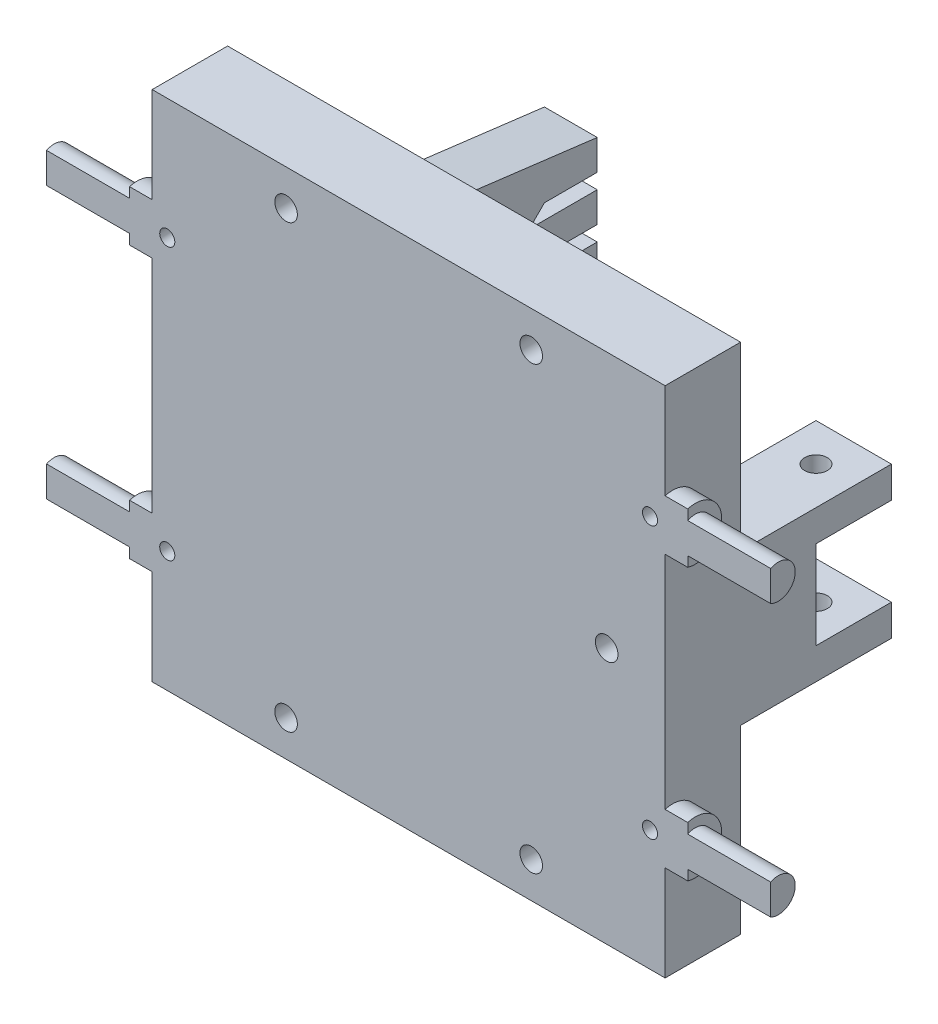
SolidWorks part; units mm, degrees
ref_plane "Front Plane" through (0, 0, 0) normal (0, 0, 1) x (1, 0, 0)
ref_plane "Top Plane" through (0, 0, 0) normal (0, 1, 0) x (1, 0, 0)
ref_plane "Right Plane" through (0, 0, 0) normal (1, 0, 0) x (0, 0, -1)
sketch "Sketch1" plane through (0, 0, 0) normal (0, 0, 1) x (1, 0, 0)
  line L1 (0, 0) -> (-68, 0)
  line L2 (0, 0) -> (0, -68)
  line L3 (0, -68) -> (-68, -68)
  line L4 (-68, 0) -> (-68, -68)
  dimension "D1" = 68
  dimension "D2" = 68
extrude "Boss-Extrude1" add sketch "Sketch1" along normal blind 10
sketch "Sketch2" plane through (-68, 0, 0) normal (-1, 0, 0) x (0, 0, 1)
  line L1 (10, 0) -> (0, 0) construction
  line L2 (10, -68) -> (0, -68) construction
  line L3 (10, 0) -> (10, -68) construction
  line L4 (10, 0) -> (10, -68)
  circle A0 centre (9, -52) radius 3.5
  circle A1 centre (9, -16) radius 3.5
  dimension "D1" = 7
  dimension "D2" = 7
  dimension "D3" = 1
  dimension "D4" = 0
  dimension "D5" = 16
  dimension "D6" = 16
extrude "Boss-Extrude2" add sketch "Sketch2" along normal blind 3 contours L4 A1 | L4 A0
sketch "Sketch3" plane through (-71, 0, 0) normal (-1, 0, 0) x (0, 0, 1)
  line L0 (10, -55.3541) -> (10, -12.6459)
  circle A0 centre (9, -52) radius 2.25
  circle A1 centre (9, -16) radius 2.25
  dimension "D1" = 4.5
  dimension "D2" = 4.5
extrude "Boss-Extrude3" add sketch "Sketch3" along normal blind 11 contours L0 A0 | L0 A1
sketch "Sketch4" plane through (0, 0, 0) normal (1, 0, 0) x (0, 0, -1)
  line L0 (-10, 0) -> (0, 0) construction
  line L1 (-10, -68) -> (0, -68) construction
  line L2 (-10, 0) -> (-10, -68)
  circle A0 centre (-9, -16) radius 3.5
  circle A1 centre (-9, -52) radius 3.5
  dimension "D1" = 16
  dimension "D2" = 16
  dimension "D3" = 7
  dimension "D4" = 7
  dimension "D5" = 1
  dimension "D6" = 0
extrude "Boss-Extrude4" add sketch "Sketch4" along normal blind 3 contours L2 A0 | L2 A1
sketch "Sketch5" plane through (3, 0, 0) normal (1, 0, 0) x (0, 0, -1)
  line L0 (-10, -12.6459) -> (-10, -55.3541)
  circle A0 centre (-9, -16) radius 2.25
  circle A1 centre (-9, -52) radius 2.25
  dimension "D1" = 4.5
  dimension "D2" = 4.5
extrude "Boss-Extrude5" add sketch "Sketch5" along normal blind 11 contours L0 A0 | L0 A1
sketch "Sketch6" plane through (0, 0, 0) normal (0, 0, -1) x (-1, 0, 0)
  line L0 (0, -34) -> (68, -34) construction
  line L1 (55.25, -12.75) -> (12.75, -12.75)
  line L2 (55.25, -12.75) -> (55.25, -55.25)
  line L3 (55.25, -55.25) -> (12.75, -55.25)
  line L4 (12.75, -12.75) -> (12.75, -55.25)
  line L5 (0, -68) -> (0, 0) construction
  line L6 (68, 0) -> (68, -68) construction
  line L7 (34, 0) -> (34, -68) construction
  line L8 (0, 0) -> (68, 0) construction
  line L9 (68, -68) -> (0, -68) construction
  point P16 (12.75, -34)
  point P17 (34, -55.25)
  dimension "D1" = 42.5
  dimension "D2" = 42.5
  dimension "D3" = 0
  dimension "D4" = 0
extrude "Cut-Extrude1" cut sketch "Sketch6" against normal blind 3
sketch "Sketch8" plane through (0, 0, 0) normal (0, 0, -1) x (-1, 0, 0)
  line L0 (55.25, -12.75) -> (12.75, -12.75) construction
  line L2 (12.75, -12.75) -> (12.75, -55.25) construction
  line L3 (34, 0) -> (34, -108.8236) construction
  line L4 (0, 0) -> (68, 0) construction
  line L5 (0, -34) -> (112.3527, -34) construction
  line L6 (0, -68) -> (0, 0) construction
  circle A0 centre (17.75, -4.75) radius 1.5
  circle A3 centre (50.25, -4.75) radius 1.5
  circle A4 centre (50.25, -63.25) radius 1.5
  circle A5 centre (17.75, -63.25) radius 1.5
  dimension "D1" = 8
  dimension "D3" = 3
  dimension "D5" = 5
extrude "Cut-Extrude2" cut sketch "Sketch8" against normal blind 15
sketch "Sketch9" plane through (0, 0, 0) normal (0, 0, -1) x (-1, 0, 0)
  line L1 (0, -24) -> (10, -24)
  line L2 (0, -24) -> (0, -44)
  line L3 (0, -44) -> (10, -44)
  line L4 (10, -24) -> (10, -44)
  line L6 (0, -68) -> (0, 0) construction
  point P4 (0, -34)
  point P7 (0, -34)
  dimension "D1" = 0
  dimension "D2" = 20
  dimension "D3" = 0
  dimension "D4" = 10
  dimension "D5" = 90
  dimension "D6" = 90
  dimension "D7" = 90
extrude "Boss-Extrude6" add sketch "Sketch9" along normal blind 20
sketch "Sketch10" plane through (0, 0, 0) normal (0, 0, -1) x (-1, 0, 0)
  line L0 (0, -56) -> (23.3312, -56) construction
  line L1 (0, -68) -> (0, -44) construction
  line L2 (12.75, -12.75) -> (12.75, -55.25) construction
  line L3 (10, -44) -> (10, -24) construction
  circle A0 centre (7.75, -34) radius 1.5
  circle A1 centre (7.75, -78) radius 1.5
  point P10 (10, -34)
  dimension "D1" = 3
  dimension "D2" = 5
  dimension "D3" = 0
extrude "Cut-Extrude3" cut sketch "Sketch10" against normal blind 10
sketch "Sketch11" plane through (0, 0, 10) normal (0, 0, 1) x (1, 0, 0)
  line L0 (-68, -34) -> (19.7059, -34) construction
  line L1 (-68, -19.3541) -> (-68, -48.6459) construction
  line L2 (-34, -68) -> (-34, 32.0149) construction
  line L3 (-68, -68) -> (0, -68) construction
  line L4 (-82, -54.0156) -> (-82, -49.9844) construction
  circle A0 centre (-66, -52) radius 1
  circle A1 centre (-66, -16) radius 1
  circle A2 centre (-2, -52) radius 1
  circle A3 centre (-2, -16) radius 1
  point P12 (-82, -52)
  dimension "D1" = 16
  dimension "D2" = 0
  dimension "D3" = 2
extrude "Cut-Extrude4" cut sketch "Sketch11" against normal blind 20
sketch "Sketch13" plane through (0, 0, 0) normal (0, 0, -1) x (-1, 0, 0)
  line L0 (68, 0) -> (68, -68) construction
  line L1 (59, -26) -> (66, -26)
  line L2 (59, -26) -> (59, -42)
  line L3 (59, -42) -> (66, -42)
  line L4 (66, -26) -> (66, -42)
  point P4 (66, -34)
  point P7 (68, -34)
  dimension "D1" = 7
  dimension "D2" = 0
  dimension "D3" = 16
  dimension "D4" = 2
extrude "Boss-Extrude7" add sketch "Sketch13" along normal blind 40
sketch "Sketch15" plane through (-66, 0, 0) normal (-1, 0, 0) x (0, 0, 1)
  line L0 (-40, -34) -> (24.0661, -34) construction
  line L1 (-40, -42) -> (-40, -26) construction
  line L2 (-40, -32) -> (-31, -32)
  line L3 (-31, -32) -> (-33, -30)
  line L4 (-33, -30) -> (-40, -30)
  line L5 (-40, -30) -> (-40, -32)
  line L6 (-40, -26) -> (0, -26) construction
  line L7 (-40, -38) -> (-40, -36)
  line L8 (-31, -36) -> (-33, -38)
  line L9 (-33, -38) -> (-40, -38)
  line L10 (-40, -36) -> (-31, -36)
  dimension "D1" = 2
  dimension "D2" = 4
  dimension "D3" = 45
  dimension "D4" = 7
extrude "Cut-Extrude5" cut sketch "Sketch15" against normal blind 10
sketch "Sketch16" plane through (-66, 0, 0) normal (-1, 0, 0) x (0, 0, 1)
  line L0 (0, -26) -> (-40, -26)
  line L1 (-40, -26) -> (0, -21)
  line L2 (0, -21) -> (0, -26)
  line L3 (-40, -34) -> (21.219, -34) construction
  line L4 (-40, -36) -> (-40, -32) construction
  line L5 (-40, -42) -> (0, -47)
  line L6 (0, -42) -> (-40, -42)
  line L7 (0, -47) -> (0, -42)
  dimension "D1" = 5
extrude "Boss-Extrude8" add sketch "Sketch16" against normal up to vertex
sketch "Sketch17" plane through (0, 0, -20) normal (0, 0, -1) x (-1, 0, 0)
  line L1 (0, -28.15) -> (10, -28.15)
  line L2 (0, -28.15) -> (0, -39.85)
  line L3 (0, -39.85) -> (10, -39.85)
  line L4 (10, -28.15) -> (10, -39.85)
  line L5 (10, -44) -> (10, -24) construction
  line L6 (0, -24) -> (0, -44) construction
  point P4 (0, -34)
  point P9 (0, -34)
  dimension "D1" = 0
  dimension "D2" = 11.7
  dimension "D3" = 0
extrude "Cut-Extrude6" cut sketch "Sketch17" against normal blind 10
sketch "Sketch18" plane through (0, -44, 0) normal (0, -1, 0) x (-1, 0, 0)
  line L0 (0, 20) -> (10, 20) construction
  line L1 (0, 10) -> (0, 20) construction
  circle A0 centre (5, 15) radius 1.5
  point P4 (5, 20)
  point P7 (0, 15)
  dimension "D1" = 0
  dimension "D2" = 0
  dimension "D3" = 3
extrude "Cut-Extrude7" cut sketch "Sketch18" against normal blind 30
